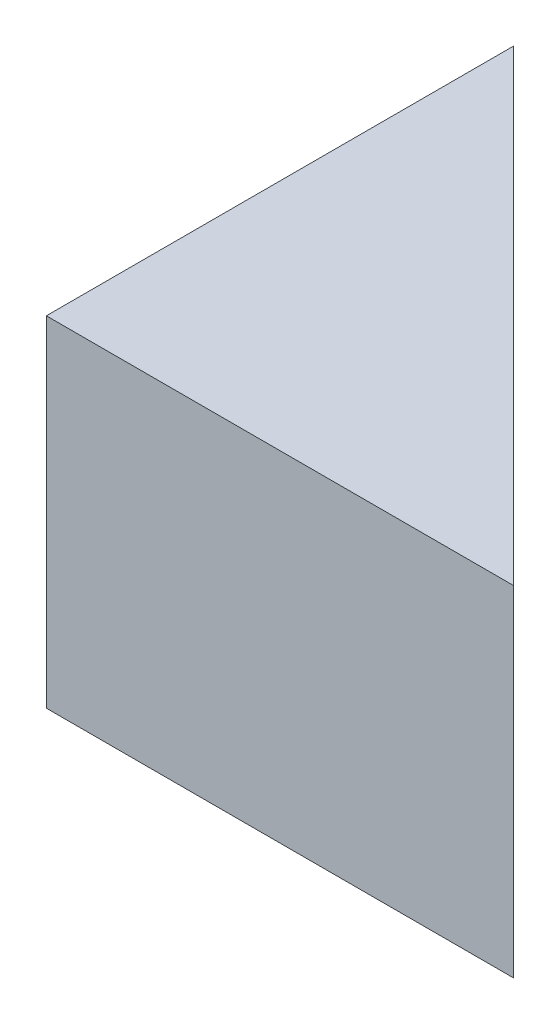
SolidWorks part; units mm, degrees
ref_plane "Front Plane" through (0, 0, 0) normal (0, 0, 1) x (1, 0, 0)
ref_plane "Top Plane" through (0, 0, 0) normal (0, 1, 0) x (1, 0, 0)
ref_plane "Right Plane" through (0, 0, 0) normal (1, 0, 0) x (0, 0, -1)
sketch "Sketch1" plane through (0, 0, 0) normal (0, 1, 0) x (1, 0, 0)
  line L0 (0, 0) -> (0, 27.5)
  line L1 (0, 27.5) -> (27.5, 0)
  line L2 (27.5, 0) -> (0, 0)
  dimension "D1" = 27.5
  dimension "D2" = 27.5
extrude "Boss-Extrude1" add sketch "Sketch1" along normal blind 20
